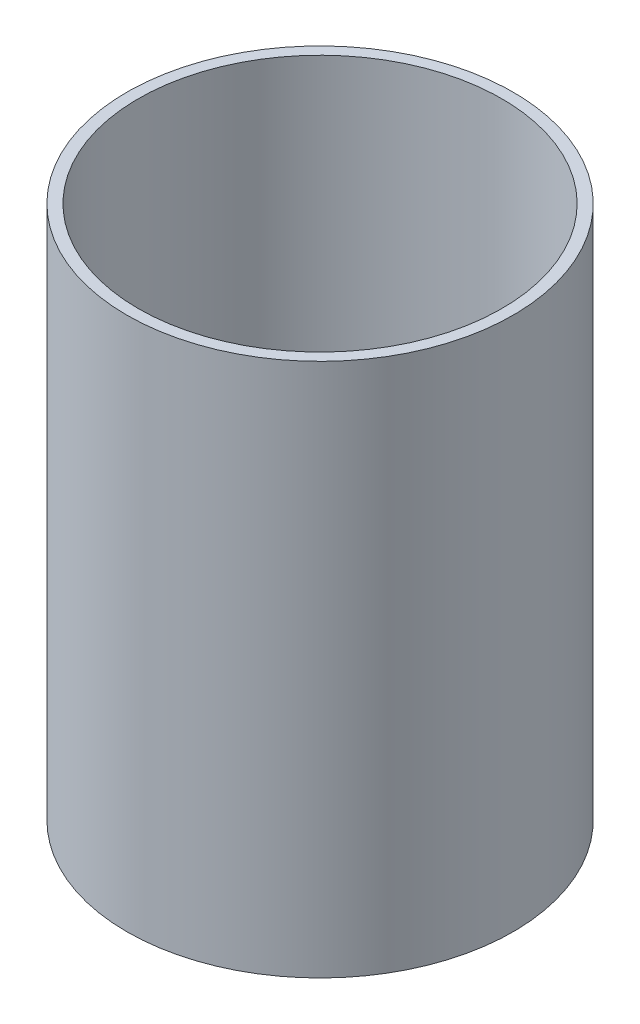
SolidWorks part; units mm, degrees
material "Acrylic (Medium-high impact)"
ref_plane "Front Plane" through (0, 0, 0) normal (0, 0, 1) x (1, 0, 0)
ref_plane "Top Plane" through (0, 0, 0) normal (0, 1, 0) x (1, 0, 0)
ref_plane "Right Plane" through (0, 0, 0) normal (1, 0, 0) x (0, 0, -1)
sketch "Sketch2" plane through (0, 0, 0) normal (0, 1, 0) x (1, 0, 0)
  circle A0 centre (0, 0) radius 101.6
  circle A1 centre (0, 0) radius 107.95
  dimension "D1" = 215.9
  dimension "D2" = 6.35
extrude "Boss-Extrude1" add sketch "Sketch2" along normal blind 298.45
